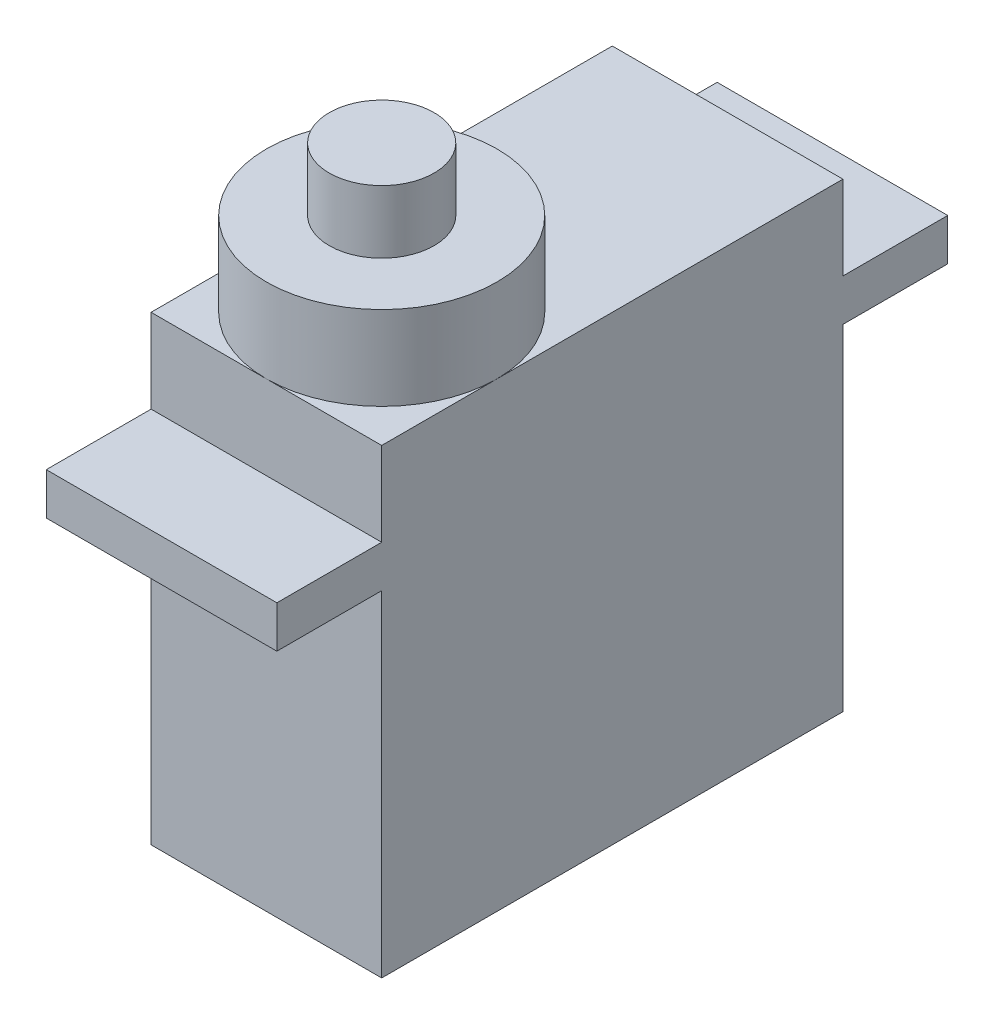
SolidWorks part; units mm, degrees
ref_plane "Front Plane" through (0, 0, 0) normal (0, 0, 1) x (1, 0, 0)
ref_plane "Top Plane" through (0, 0, 0) normal (0, 1, 0) x (1, 0, 0)
ref_plane "Right Plane" through (0, 0, 0) normal (1, 0, 0) x (0, 0, -1)
sketch "Sketch1" plane through (0, 0, 0) normal (0, 1, 0) x (1, 0, 0)
  line L1 (5.5, -11) -> (-5.5, -11)
  line L2 (5.5, -11) -> (5.5, 11)
  line L3 (5.5, 11) -> (-5.5, 11)
  line L4 (-5.5, -11) -> (-5.5, 11)
  line L5 (5.5, -11) -> (-5.5, 11) construction
  line L6 (5.5, 11) -> (-5.5, -11) construction
  point P0 (0, 0)
  dimension "D1" = 22
  dimension "D2" = 11
extrude "Boss-Extrude1" add sketch "Sketch1" along normal blind 22
sketch "Sketch2" plane through (0, 22, 0) normal (0, 1, 0) x (1, 0, 0)
  line L1 (-5.5, 11) -> (-5.5, -11) construction
  line L2 (5.5, -11) -> (5.5, 11) construction
  line L3 (-5.5, -11) -> (5.5, -11) construction
  circle A1 centre (0, -5.5) radius 5.5
sketch "Sketch3" plane through (0, 0, -11) normal (0, 0, -1) x (-1, 0, 0)
  line L0 (-5.5, 22) -> (-5.5, 0) construction
  line L1 (-5.5, 18) -> (5.5, 18)
  line L2 (-5.5, 18) -> (-5.5, 16)
  line L3 (-5.5, 16) -> (5.5, 16)
  line L4 (5.5, 18) -> (5.5, 16)
  line L5 (5.5, 22) -> (5.5, 0) construction
  line L6 (-5.5, 22) -> (5.5, 22) construction
  dimension "D1" = 4
  dimension "D2" = 2
extrude "Boss-Extrude3" add sketch "Sketch3" along normal blind 5 contours L3 L4 L1 L2
ref_plane "Plane1" through (0, 0, 0) normal (0, 0, 1) x (1, 0, 0)
mirror "Mirror1" about plane through (0, 0, 0) normal (0, 0, 1) of "Boss-Extrude3"
extrude "Boss-Extrude4" add sketch "Sketch2" along normal blind 4 contours A1
sketch "Sketch4" plane through (0, 26, 0) normal (0, 1, 0) x (1, 0, 0)
  circle A0 centre (0, -5.5) radius 2.5
  dimension "D1" = 5
extrude "Boss-Extrude5" add sketch "Sketch4" along normal blind 3
